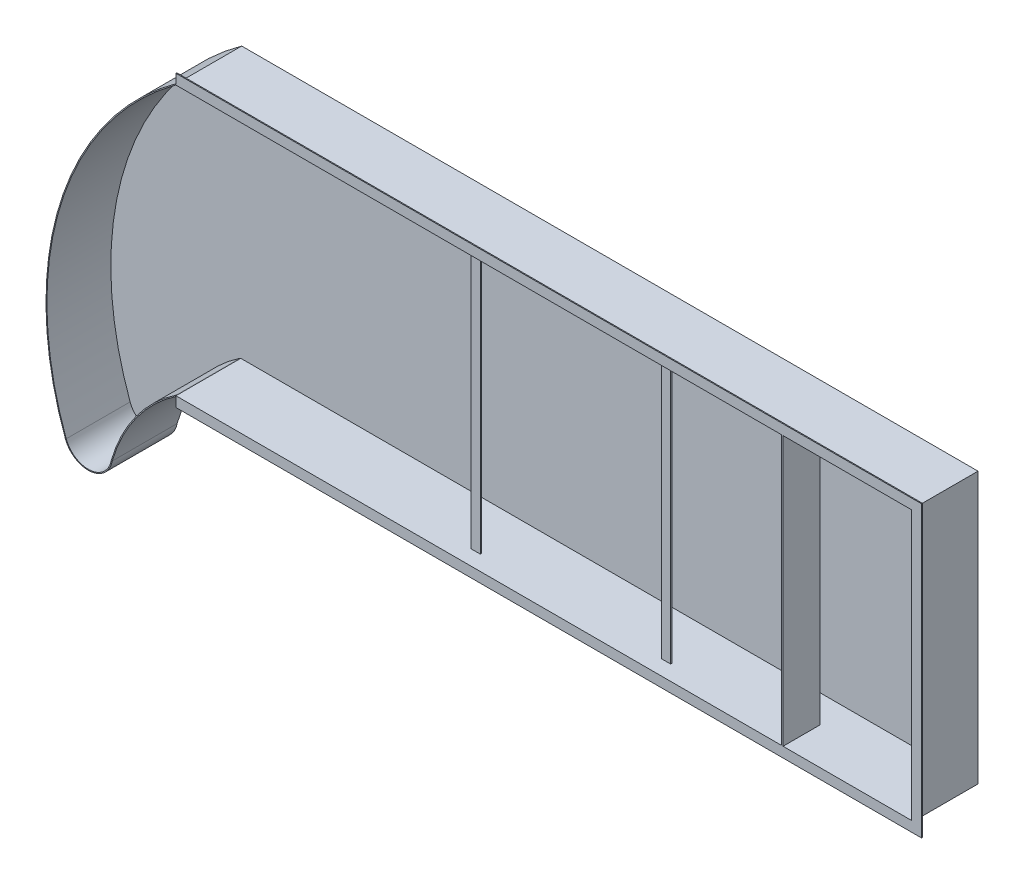
SolidWorks part; units mm, degrees
ref_plane "前视基准面" through (0, 0, 0) normal (0, 0, 1) x (1, 0, 0)
ref_plane "上视基准面" through (0, 0, 0) normal (0, 1, 0) x (1, 0, 0)
ref_plane "右视基准面" through (0, 0, 0) normal (1, 0, 0) x (0, 0, -1)
sketch "草图1" plane through (0, 0, 0) normal (0, 0, 1) x (1, 0, 0)
  line L1 (-795, -292.5) -> (795, -292.5)
  line L2 (-795, -292.5) -> (-795, 292.5)
  line L3 (-795, 292.5) -> (795, 292.5)
  line L4 (795, -292.5) -> (795, 292.5)
  line L5 (-795, -292.5) -> (795, 292.5) construction
  line L6 (-795, 292.5) -> (795, -292.5) construction
  point P0 (0, 0)
  dimension "D1" = 1590
  dimension "D2" = 585
extrude "凸台-拉伸1" add sketch "草图1" along normal blind 2
sketch "草图2" plane through (0, 0, 2) normal (0, 0, 1) x (1, 0, 0)
  line L0 (-795, -290.5) -> (793, -290.5)
  line L1 (793, -290.5) -> (793, 290.5)
  line L2 (793, 290.5) -> (-795, 290.5)
  line L3 (-795, -290.5) -> (-795, -292.5)
  line L4 (795, -292.5) -> (795, 292.5)
  line L5 (795, 292.5) -> (-795, 292.5)
  line L6 (-795, 292.5) -> (-795, -292.5)
  line L7 (-795, -292.5) -> (795, -292.5)
  line L8 (795, -292.5) -> (795, 292.5)
  line L9 (795, 292.5) -> (-795, 292.5)
  line L10 (-795, 292.5) -> (-795, 290.5)
  line L11 (-795, -292.5) -> (795, -292.5)
  dimension "D1" = 0
  dimension "D2" = 2
extrude "凸台-拉伸2" add sketch "草图2" along normal blind 140
sketch "草图3" plane through (0, -292.5, 0) normal (0, -1, 0) x (1, 0, 0)
  line L0 (795, 142) -> (795, 0) construction
  line L1 (-795, 142) -> (-795, 0) construction
  line L2 (-795, 142) -> (795, 142) construction
  line L3 (795, 142) -> (795, 140)
  line L4 (-795, 142) -> (-795, 140)
  line L5 (-795, 142) -> (795, 142)
  line L6 (-795, 140) -> (795, 140)
  dimension "D1" = 2
extrude "凸台-拉伸3" add sketch "草图3" along normal blind 20
mirror "镜向1" about plane through (0, 0, 0) normal (0, 1, 0) of "凸台-拉伸3"
sketch "草图4" plane through (795, 0, 0) normal (1, 0, 0) x (0, 0, -1)
  line L0 (-140, 292.5) -> (-140, -292.5)
  line L8 (0, -292.5) -> (0, 292.5)
  line L9 (0, 292.5) -> (-140, 292.5)
  line L10 (-140, 292.5) -> (-140, 312.5)
  line L11 (-140, 312.5) -> (-142, 312.5)
  line L12 (-142, 312.5) -> (-142, -312.5)
  line L13 (-142, -312.5) -> (-140, -312.5)
  line L14 (-140, -312.5) -> (-140, -292.5)
  line L15 (-140, -292.5) -> (0, -292.5)
  line L18 (-140, 292.5) -> (-140, 312.5)
  line L19 (-140, 312.5) -> (-142, 312.5)
  line L20 (-142, 312.5) -> (-142, -312.5)
  line L21 (-142, -312.5) -> (-140, -312.5)
  line L22 (-140, -312.5) -> (-140, -292.5)
  dimension "D1" = 0
extrude "凸台-拉伸4" add sketch "草图4" along normal blind 20
sketch "草图5" plane through (0, 0, 0) normal (0, 0, -1) x (-1, 0, 0)
  line L0 (795, 290.5) -> (795, -290.5) construction
  line L1 (795, 292.5) -> (795, -292.5)
  arc A0 (1035.7914, -492.1668) -> (795, 292.5) centre (400.3549, -257.8844) ccw
  arc A1 (934.5629, -483.4694) -> (795, -292.5) centre (604.8436, -577.9506) ccw
  arc A2 (934.5629, -483.4694) -> (1035.7914, -492.1668) centre (986.3691, -473.945) ccw
  point P3 (1002.886, -520.097)
  point P4 (965.6328, -523.3856)
  point P5 (0, 0)
  point P7 (969.9996, -485.9391)
  point P11 (1034.4569, -484.4229)
  point P12 (934.5629, -483.4694)
  point P15 (795, 292.1282)
  point P16 (0, 0)
  point P17 (0, 0)
  point P18 (0, 0)
  point P19 (0, 0)
  point P20 (795, -292.2217)
extrude "凸台-拉伸5" add sketch "草图5" against normal blind 140 contours A0 L1 A1 A2
sketch "草图6" plane through (0, 0, 140) normal (0, 0, 1) x (1, 0, 0)
  line L0 (-795, -290.5) -> (-797, -291.4312)
  line L1 (-797, 288.591) -> (-797, 288.591)
  line L2 (-795, 290.5) -> (-797, 288.591)
  line L3 (-795, -292.5) -> (-795, -290.5)
  line L4 (-795, -290.5) -> (-795, 290.5)
  line L5 (-795, 290.5) -> (-795, 292.5)
  line L6 (-795, -292.5) -> (-795, -290.5)
  line L7 (-795, -290.5) -> (-795, 290.5)
  line L8 (-795, 290.5) -> (-795, 292.5)
  line L12 (-797, -290.5) -> (-797, 288.591) construction
  line L13 (-797, -291.4312) -> (-797, -290.5) construction
  arc A0 (-797, 288.591) -> (-1033.9149, -491.4749) centre (-400.3549, -257.8844) ccw
  arc A1 (-1033.9149, -491.4749) -> (-936.5126, -483.0131) centre (-986.3691, -473.945) ccw
  arc A2 (-797, -291.4312) -> (-936.5126, -483.0131) centre (-604.8436, -577.9506) ccw
  arc A3 (-1035.7914, -492.1668) -> (-934.5629, -483.4694) centre (-986.3691, -473.945) ccw
  arc A4 (-795, -292.5) -> (-934.5629, -483.4694) centre (-604.8436, -577.9506) ccw
  arc A5 (-795, 292.5) -> (-1035.7914, -492.1668) centre (-400.3549, -257.8844) ccw
  arc A6 (-1035.7914, -492.1668) -> (-934.5629, -483.4694) centre (-986.3691, -473.945) ccw construction
  arc A7 (-795, -292.5) -> (-934.5629, -483.4694) centre (-604.8436, -577.9506) ccw construction
  arc A8 (-795, 292.5) -> (-1035.7914, -492.1668) centre (-400.3549, -257.8844) ccw construction
  dimension "D1" = 0
  dimension "D2" = 2
extrude "切除-拉伸1" cut sketch "草图6" against normal blind 138
sketch "草图8" plane through (0, 290.5, 0) normal (0, -1, 0) x (1, 0, 0)
  line L1 (-190.0657, 109.5714) -> (-170.0657, 109.5714)
  line L2 (-190.0657, 109.5714) -> (-190.0657, 106.5714)
  line L3 (-190.0657, 106.5714) -> (-170.0657, 106.5714)
  line L4 (-170.0657, 109.5714) -> (-170.0657, 106.5714)
  line L5 (-190.0657, 109.5714) -> (-170.0657, 106.5714) construction
  line L6 (-190.0657, 106.5714) -> (-170.0657, 109.5714) construction
  line L7 (220.6769, 109.5714) -> (240.6769, 109.5714)
  line L8 (220.6769, 109.5714) -> (220.6769, 106.5714)
  line L9 (220.6769, 106.5714) -> (240.6769, 106.5714)
  line L10 (240.6769, 109.5714) -> (240.6769, 106.5714)
  line L11 (220.6769, 109.5714) -> (240.6769, 106.5714) construction
  line L12 (220.6769, 106.5714) -> (240.6769, 109.5714) construction
  point P0 (-180.0657, 108.0714)
  point P5 (230.6769, 108.0714)
  point P10 (0, 0)
  point P11 (0, 0)
  point P12 (-172.0938, 131.2321)
  point P13 (230.6769, 93.6528)
  point P14 (-180.0657, 109.5714)
  dimension "D1" = 20
  dimension "D2" = 3
  dimension "D3" = 3
  dimension "D4" = 20
extrude "凸台-拉伸6" add sketch "草图8" along normal up to surface (581 mm away) up to face at (-159.8, -290.5, 85.6)
sketch "草图9" plane through (0, 290.5, 0) normal (0, -1, 0) x (1, 0, 0)
  line L0 (513, 142) -> (513, 62)
  line L1 (-795, 142) -> (793, 142) construction
  line L2 (793, 142) -> (-795, 142) construction
  line L3 (513, 142) -> (516, 142)
  line L4 (793, 142) -> (-795, 142)
  line L6 (793, 142) -> (793, 2) construction
  line L8 (516, 142) -> (516, 62)
  line L9 (516, 62) -> (513, 62)
  line L11 (516, 142) -> (516, 2) construction
  line L12 (513, 142) -> (513, 2) construction
  dimension "D1" = 280
  dimension "D3" = 80
  dimension "D2" = 3
extrude "凸台-拉伸7" add sketch "草图9" along normal up to surface (581 mm away) contours L8 L9 L0 L3 up to face at (-180.0657, -290.5, 108.0714)
